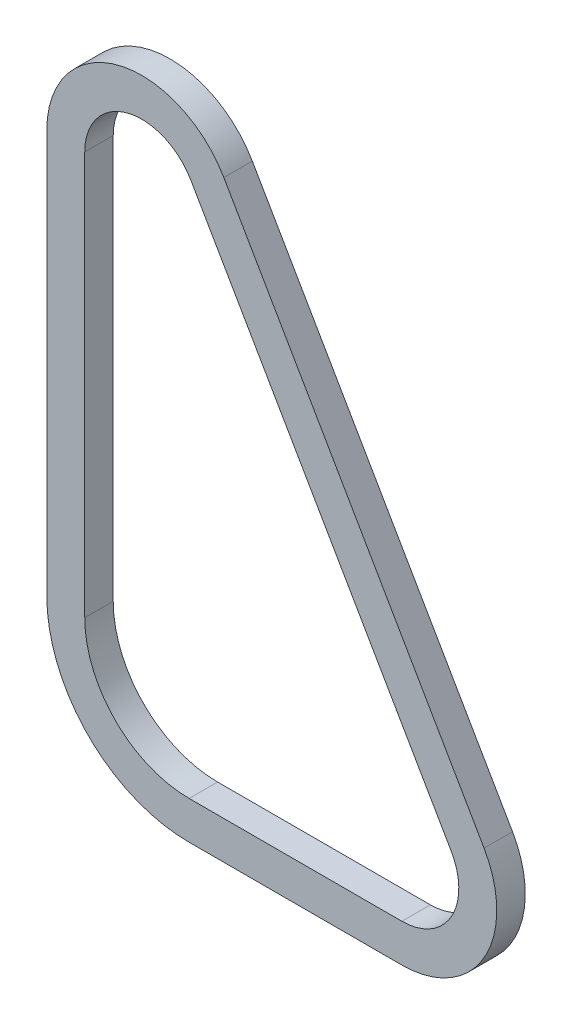
SolidWorks part; units mm, degrees
ref_plane "Front Plane" through (0, 0, 0) normal (0, 0, 1) x (1, 0, 0)
ref_plane "Top Plane" through (0, 0, 0) normal (0, 1, 0) x (1, 0, 0)
ref_plane "Right Plane" through (0, 0, 0) normal (1, 0, 0) x (0, 0, -1)
sketch "Sketch1" plane through (0, 0, 0) normal (0, 0, 1) x (1, 0, 0)
  line L0 (0, -425) -> (0, 0)
  line L1 (93.3013, 25) -> (367.5426, -450)
  line L2 (324.2414, -525) -> (100, -525)
  line L3 (-353.0078, 50) -> (50, 50) construction
  line L13 (136.6025, 50) -> (410.8439, -425)
  line L14 (324.2414, -575) -> (100, -575)
  line L15 (-50, -425) -> (-50, 0)
  line L16 (101.9615, 30) -> (376.2029, -445)
  line L17 (324.2414, -535) -> (100, -535)
  line L18 (-10, -425) -> (-10, 0)
  arc A0 (0, -425) -> (100, -525) centre (100, -425) ccw
  arc A1 (0, 0) -> (93.3013, 25) centre (50, 0) cw
  arc A2 (367.5426, -450) -> (324.2414, -525) centre (324.2414, -475) cw
  arc A12 (-50, 0) -> (136.6025, 50) centre (50, 0) cw
  arc A13 (410.8439, -425) -> (324.2414, -575) centre (324.2414, -475) cw
  arc A14 (-50, -425) -> (100, -575) centre (100, -425) ccw
  arc A15 (-10, 0) -> (101.9615, 30) centre (50, 0) cw
  arc A16 (376.2029, -445) -> (324.2414, -535) centre (324.2414, -475) cw
  arc A17 (-10, -425) -> (100, -535) centre (100, -425) ccw
  point P20 (0, 0)
  point P21 (0, 0)
  point P23 (0, 0)
  point P24 (0, 0)
  point P25 (0, 0)
  dimension "D1" = 100
  dimension "D2" = 50
  dimension "D3" = 575
  dimension "D4" = 60
  dimension "D5" = 50
  dimension "D6" = 10
extrude "Boss-Extrude3" add sketch "Sketch1" along normal blind 30
